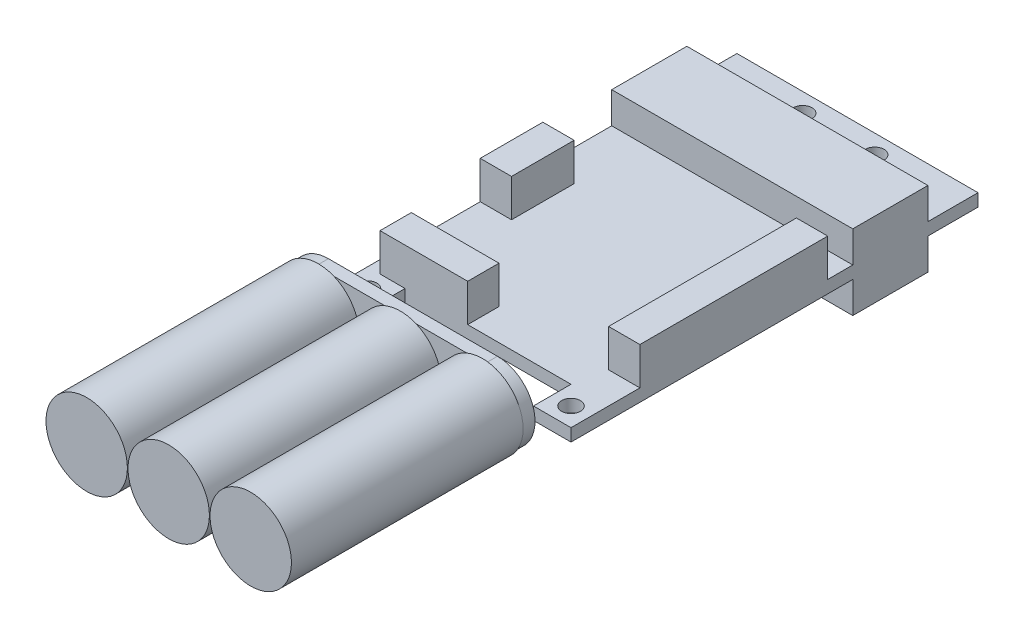
SolidWorks part; units mm, degrees
ref_plane "정면" through (0, 0, 0) normal (0, 0, 1) x (1, 0, 0)
ref_plane "윗면" through (0, 0, 0) normal (0, 1, 0) x (1, 0, 0)
ref_plane "우측면" through (0, 0, 0) normal (1, 0, 0) x (0, 0, -1)
sketch "스케치1" plane through (0, 0, 0) normal (0, 1, 0) x (1, 0, 0)
  line L0 (0, 29.5) -> (0, -29.5) construction
  line L1 (19.25, 29.5) -> (-19.25, 29.5)
  line L2 (19.25, 29.5) -> (19.25, -29.5)
  line L3 (19.25, -29.5) -> (-19.25, -29.5)
  line L4 (-19.25, 29.5) -> (-19.25, -29.5)
  line L5 (19.25, 29.5) -> (-19.25, -29.5) construction
  line L6 (19.25, -29.5) -> (-19.25, 29.5) construction
  line L7 (-13.25, -29.5) -> (-19.25, -35.5) construction
  line L8 (13.25, -35.5) -> (19.25, -35.5)
  line L9 (13.25, -35.5) -> (13.25, -29.5)
  line L10 (13.25, -29.5) -> (19.25, -29.5)
  line L11 (19.25, -35.5) -> (19.25, -29.5)
  line L12 (13.25, -35.5) -> (19.25, -29.5) construction
  line L13 (13.25, -29.5) -> (19.25, -35.5) construction
  line L14 (-13.25, -35.5) -> (-19.25, -29.5) construction
  line L15 (-19.25, -35.5) -> (-19.25, -29.5)
  line L16 (-13.25, -29.5) -> (-19.25, -29.5)
  line L17 (-13.25, -35.5) -> (-13.25, -29.5)
  line L18 (-13.25, -35.5) -> (-19.25, -35.5)
  point P0 (0, 0)
  point P8 (16.25, -32.5)
  point P15 (-16.25, -32.5)
  dimension "D1" = 38.5
  dimension "D2" = 59
  dimension "D3" = 6
extrude "보스-돌출1" add sketch "스케치1" along normal blind 2 contours L1 L4 L3 L2 | L18 L17 L3 L15 | L8 L11 L3 L9
sketch "스케치2" plane through (0, 2, 0) normal (0, 1, 0) x (1, 0, 0)
  line L1 (0, 29.5) -> (0, -29.5) construction
  line L2 (0, 29.5) -> (0, -29.5) construction
  line L3 (-19.25, 29.5) -> (-19.25, -29.5) construction
  line L4 (19.25, 29.5) -> (-19.25, 29.5) construction
  circle A0 centre (-16.25, -32.5) radius 1.5
  circle A1 centre (5.75, 26.5) radius 1.5
  circle A2 centre (-5.75, 26.5) radius 1.5
  circle A3 centre (16.25, -32.5) radius 1.5
  dimension "D1" = 3
  dimension "D2" = 12
  dimension "D3" = 3
extrude "컷-돌출1" cut sketch "스케치2" against normal through all
sketch "스케치3" plane through (0, 2, 0) normal (0, 1, 0) x (1, 0, 0)
  line L0 (19.25, 29.5) -> (19.25, -35.5) construction
  line L1 (14.25, 5.5) -> (19.25, 5.5)
  line L2 (14.25, 5.5) -> (14.25, -24.5)
  line L3 (14.25, -24.5) -> (19.25, -24.5)
  line L4 (19.25, 5.5) -> (19.25, -24.5)
  line L5 (-19.25, 29.5) -> (-19.25, -35.5) construction
  line L6 (-19.25, -1.5) -> (-14.25, -1.5)
  line L7 (-19.25, -1.5) -> (-19.25, -11.5)
  line L8 (-19.25, -11.5) -> (-14.25, -11.5)
  line L9 (-14.25, -1.5) -> (-14.25, -11.5)
  line L10 (13.25, -29.5) -> (-13.25, -29.5) construction
  line L11 (-3.25, -29.5) -> (-17.25, -29.5)
  line L12 (-3.25, -29.5) -> (-3.25, -24.5)
  line L13 (-3.25, -24.5) -> (-17.25, -24.5)
  line L14 (-17.25, -29.5) -> (-17.25, -24.5)
  line L15 (19.25, 29.5) -> (-19.25, 29.5) construction
  dimension "D1" = 30
  dimension "D2" = 5
  dimension "D3" = 24
  dimension "D4" = 14
  dimension "D5" = 2
  dimension "D6" = 10
  dimension "D7" = 13
extrude "보스-돌출2" add sketch "스케치3" along normal blind 6
sketch "스케치4" plane through (0, 2, 0) normal (0, 1, 0) x (1, 0, 0)
  line L0 (-19.25, 29.5) -> (-19.25, -1.5) construction
  line L1 (-19.25, 21.5) -> (19.25, 21.5)
  line L2 (-19.25, 21.5) -> (-19.25, 9.5)
  line L3 (-19.25, 9.5) -> (19.25, 9.5)
  line L4 (19.25, 21.5) -> (19.25, 9.5)
  line L5 (19.25, 29.5) -> (19.25, 5.5) construction
  line L6 (19.25, 29.5) -> (-19.25, 29.5) construction
  dimension "D1" = 12
  dimension "D2" = 20
extrude "보스-돌출3" add sketch "스케치4" along normal blind 5
sketch "스케치5" plane through (0, 0, 0) normal (0, -1, 0) x (1, 0, 0)
  line L0 (19.25, -29.5) -> (19.25, 35.5) construction
  line L1 (-19.25, -21.5) -> (19.25, -21.5)
  line L2 (-19.25, -21.5) -> (-19.25, -9.5)
  line L3 (-19.25, -9.5) -> (19.25, -9.5)
  line L4 (19.25, -21.5) -> (19.25, -9.5)
  line L5 (-19.25, -29.5) -> (-19.25, 35.5) construction
  line L6 (-19.25, -21.5) -> (-19.25, -9.5) construction
extrude "보스-돌출4" add sketch "스케치5" along normal blind 5
ref_plane "평면1" through (0, 0, 41.5) normal (0, 0, 1) x (1, 0, 0)
sketch "스케치6" plane through (0, 0, 41.5) normal (0, 0, 1) x (1, 0, 0)
  line L0 (-13.5, 6) -> (13.5, 6) construction
  line L1 (-13.5, 12) -> (13.5, 12)
  line L2 (-13.5, 0) -> (13.5, 0)
  line L3 (13.25, 0) -> (-13.25, 0) construction
  arc A0 (-13.5, 12) -> (-13.5, 0) centre (-13.5, 6) ccw
  arc A1 (13.5, 0) -> (13.5, 12) centre (13.5, 6) ccw
  point P2 (0, 6)
  dimension "D2" = 39
  dimension "D1" = 12
extrude "보스-돌출5" add sketch "스케치6" along normal blind 2 separate body
sketch "스케치7" plane through (0, 0, 43.5) normal (0, 0, 1) x (1, 0, 0)
  line L0 (0, 0) -> (0, 12) construction
  line L1 (13.5, 12) -> (-13.5, 12) construction
  circle A0 centre (-13.1, 6) radius 6.5
  circle A1 centre (0, 6) radius 6.5
  circle A2 centre (13.1, 6) radius 6.5
  dimension "D1" = 13
  dimension "D2" = 0.1
extrude "보스-돌출7" add sketch "스케치7" along normal blind 37
